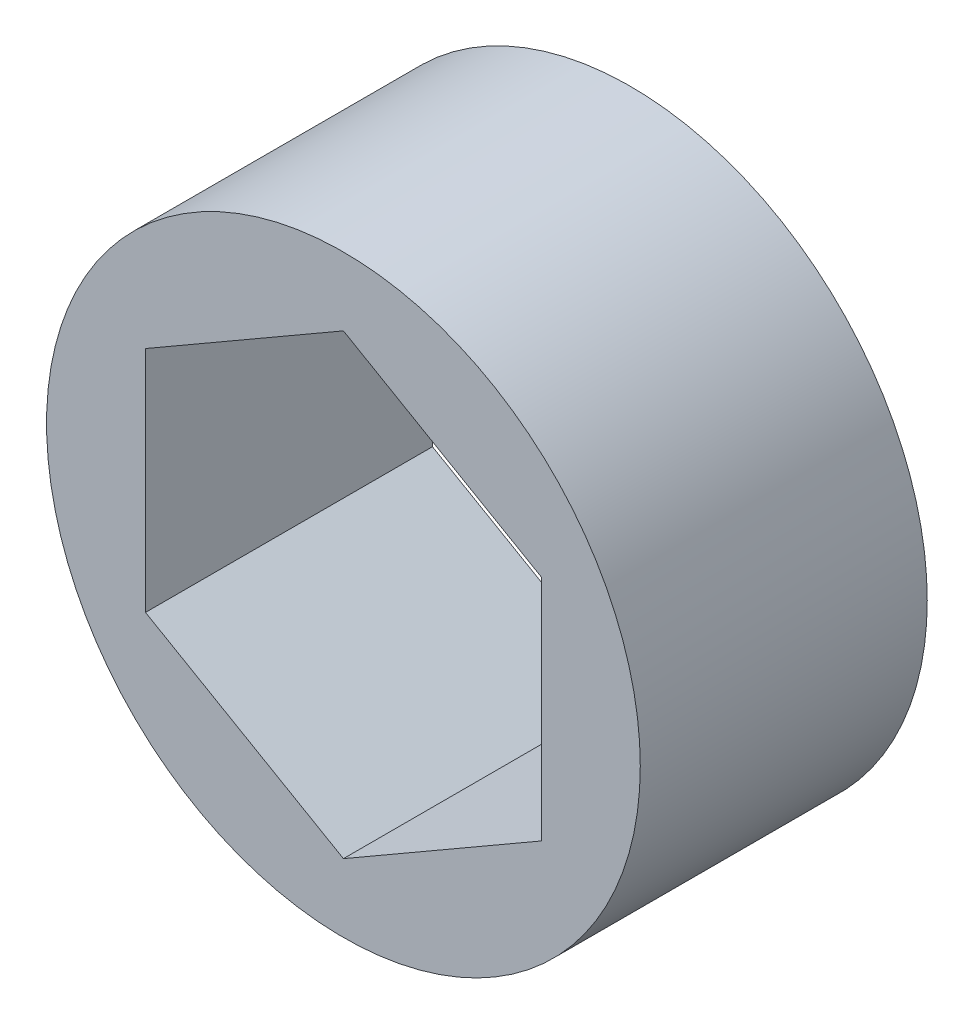
SolidWorks part; units mm, degrees
material "PET"
ref_plane "Front Plane" through (0, 0, 0) normal (0, 0, 1) x (1, 0, 0)
ref_plane "Top Plane" through (0, 0, 0) normal (0, 1, 0) x (1, 0, 0)
ref_plane "Right Plane" through (0, 0, 0) normal (1, 0, 0) x (0, 0, -1)
sketch "Sketch2" plane through (0, 0, 0) normal (0, 0, 1) x (1, 0, 0)
  line L1 (6.35, 3.6662) -> (0, 7.3323)
  line L2 (0, 7.3323) -> (-6.35, 3.6662)
  line L3 (-6.35, 3.6662) -> (-6.35, -3.6662)
  line L4 (-6.35, -3.6662) -> (0, -7.3323)
  line L5 (0, -7.3323) -> (6.35, -3.6662)
  line L6 (6.35, -3.6662) -> (6.35, 3.6662)
  circle A0 centre (0, 0) radius 9.525
  circle A1 centre (0, 0) radius 6.35 construction
  dimension "D1" = 19.05
  dimension "D2" = 12.7
extrude "Boss-Extrude1" add sketch "Sketch2" along normal blind 9.2075
